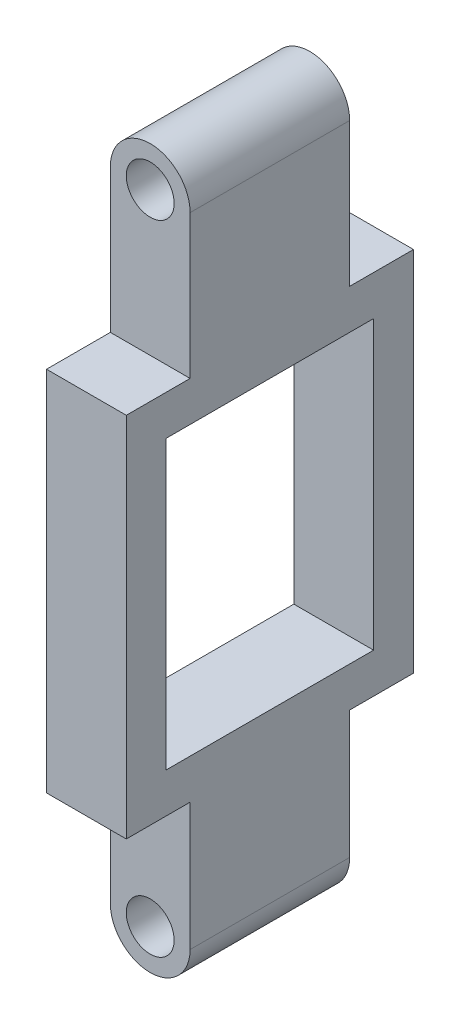
SolidWorks part; units mm, degrees
ref_plane "Piano frontale" through (0, 0, 0) normal (0, 0, 1) x (1, 0, 0)
ref_plane "Piano superiore" through (0, 0, 0) normal (0, 1, 0) x (1, 0, 0)
ref_plane "Piano destro" through (0, 0, 0) normal (1, 0, 0) x (0, 0, -1)
sketch "Schizzo1" plane through (0, 0, 0) normal (0, 0, 1) x (1, 0, 0)
  line L0 (0, 384.8889) -> (0, -15.1111) construction
  line L1 (25, 384.8889) -> (25, -15.1111)
  line L2 (-25, 384.8889) -> (-25, -15.1111)
  arc A0 (25, 384.8889) -> (-25, 384.8889) centre (0, 384.8889) ccw
  arc A1 (-25, -15.1111) -> (25, -15.1111) centre (0, -15.1111) ccw
  circle A2 centre (0, 384.8889) radius 15
  circle A3 centre (0, -15.1111) radius 15
  point P3 (0, 184.8889)
  dimension "D1" = 30
  dimension "D2" = 30
  dimension "D3" = 50
  dimension "D4" = 400
extrude "Estrusione-Estrusione1" add sketch "Schizzo1" along normal mid plane 100
sketch "Schizzo2" plane through (0, 0, 50) normal (0, 0, 1) x (1, 0, 0)
  line L0 (-25, 294.8889) -> (25, 294.8889)
  line L1 (-25, 64.8889) -> (25, 64.8889)
  line L2 (-25, 384.8889) -> (-25, -15.1111)
  line L3 (25, -15.1111) -> (25, 384.8889)
  line L4 (-25, 384.8889) -> (-25, -15.1111)
  line L5 (25, -15.1111) -> (25, 384.8889)
  arc A2 (25, 384.8889) -> (-25, 384.8889) centre (0, 384.8889) ccw
  arc A3 (-25, -15.1111) -> (25, -15.1111) centre (0, -15.1111) ccw
  arc A4 (25, 384.8889) -> (-25, 384.8889) centre (0, 384.8889) ccw
  arc A5 (-25, -15.1111) -> (25, -15.1111) centre (0, -15.1111) ccw
  line M9 (-25, 384.8889) -> (-25, -15.1111)
  line M11 (25, -15.1111) -> (25, 384.8889)
  dimension "D2" = 90
  dimension "D3" = 80
  dimension "D1" = 0
extrude "Estrusione-Estrusione2" add sketch "Schizzo2" along normal blind 40 contours L1 L0 M9 M11
mirror "Specchia1" about plane through (0, 0, 0) normal (0, 0, 1) of "Estrusione-Estrusione2"
sketch "Schizzo3" plane through (25, 0, 0) normal (1, 0, 0) x (0, 0, -1)
  line L0 (-90, 64.8889) -> (-90, 294.8889) construction
  line L1 (-65, 269.8889) -> (65, 269.8889)
  line L2 (-65, 269.8889) -> (-65, 89.8889)
  line L3 (-65, 89.8889) -> (65, 89.8889)
  line L4 (65, 269.8889) -> (65, 89.8889)
  line L5 (90, 64.8889) -> (90, 294.8889) construction
  line L6 (-90, 294.8889) -> (-50, 294.8889) construction
  line L7 (-90, 64.8889) -> (-50, 64.8889) construction
  dimension "D1" = 25
  dimension "D2" = 25
  dimension "D3" = 25
  dimension "D4" = 25
extrude "Taglio-Estrusione1" cut sketch "Schizzo3" against normal through all
